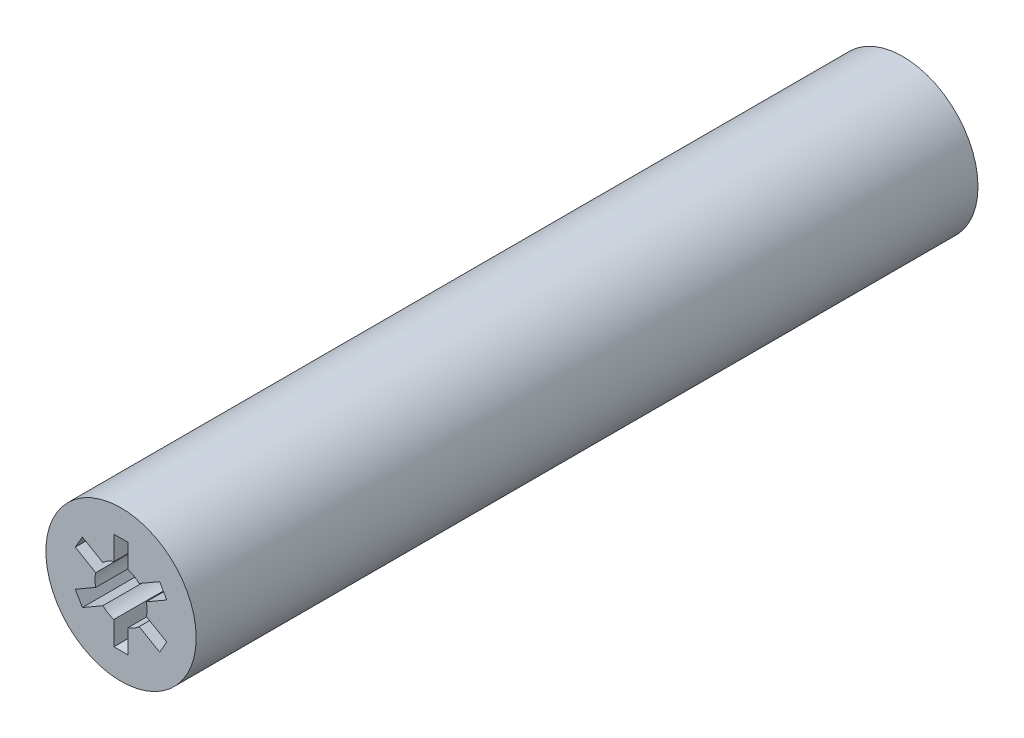
SolidWorks part; units mm, degrees
ref_plane "Front Plane" through (0, 0, 0) normal (0, 0, 1) x (1, 0, 0)
ref_plane "Top Plane" through (0, 0, 0) normal (0, 1, 0) x (1, 0, 0)
ref_plane "Right Plane" through (0, 0, 0) normal (1, 0, 0) x (0, 0, -1)
sketch "Sketch1" plane through (0, 0, 0) normal (0, 0, 1) x (1, 0, 0)
  line L0 (0, -14.4086) -> (0, 14.4086) construction
  line L1 (-1.5, 5.2915) -> (-1.5, 10.2915)
  line L2 (-1.5, 10.2915) -> (1.5, 10.2915)
  line L3 (1.5, 10.2915) -> (1.5, 5.2915)
  line L4 (3.8326, 3.9448) -> (8.1627, 6.4448)
  line L5 (8.1627, 6.4448) -> (9.6627, 3.8467)
  line L6 (9.6627, 3.8467) -> (5.3326, 1.3467)
  line L7 (5.3326, -1.3467) -> (9.6627, -3.8467)
  line L8 (9.6627, -3.8467) -> (8.1627, -6.4448)
  line L9 (8.1627, -6.4448) -> (3.8326, -3.9448)
  line L10 (1.5, -5.2915) -> (1.5, -10.2915)
  line L11 (1.5, -10.2915) -> (-1.5, -10.2915)
  line L12 (-1.5, -10.2915) -> (-1.5, -5.2915)
  line L13 (-3.8326, -3.9448) -> (-8.1627, -6.4448)
  line L14 (-8.1627, -6.4448) -> (-9.6627, -3.8467)
  line L15 (-9.6627, -3.8467) -> (-5.3326, -1.3467)
  line L16 (-5.3326, 1.3467) -> (-9.6627, 3.8467)
  line L17 (-9.6627, 3.8467) -> (-8.1627, 6.4448)
  line L18 (-8.1627, 6.4448) -> (-3.8326, 3.9448)
  circle A0 centre (0, 0) radius 15.875
  arc A1 (-5.3326, 1.3467) -> (-5.3326, -1.3467) centre (0, 0) ccw
  arc A2 (-1.5, 5.2915) -> (-3.8326, 3.9448) centre (0, 0) ccw
  arc A3 (3.8326, 3.9448) -> (1.5, 5.2915) centre (0, 0) ccw
  arc A4 (5.3326, -1.3467) -> (5.3326, 1.3467) centre (0, 0) ccw
  arc A5 (1.5, -5.2915) -> (3.8326, -3.9448) centre (0, 0) ccw
  arc A6 (-3.8326, -3.9448) -> (-1.5, -5.2915) centre (0, 0) ccw
  point P4 (1.5, 5.2915)
  point P7 (5.3326, 1.3467)
  point P8 (0, 0)
  point P11 (-1.5, 5.2915)
  point P18 (3.8326, 3.9448)
  point P21 (3.8326, -3.9448)
  point P24 (5.3326, -1.3467)
  point P27 (-1.5, -5.2915)
  point P30 (1.5, -5.2915)
  point P33 (-5.3326, -1.3467)
  point P36 (-3.8326, -3.9448)
  point P39 (-3.8326, 3.9448)
  point P42 (-5.3326, 1.3467)
  point P45 (0, 0)
  dimension "D1" = 31.75
  dimension "D2" = 11
  dimension "D5" = 6
  dimension "D4" = 5
  dimension "D3" = 1.5
extrude "Boss-Extrude1" add sketch "Sketch1" along normal mid plane 165.1
